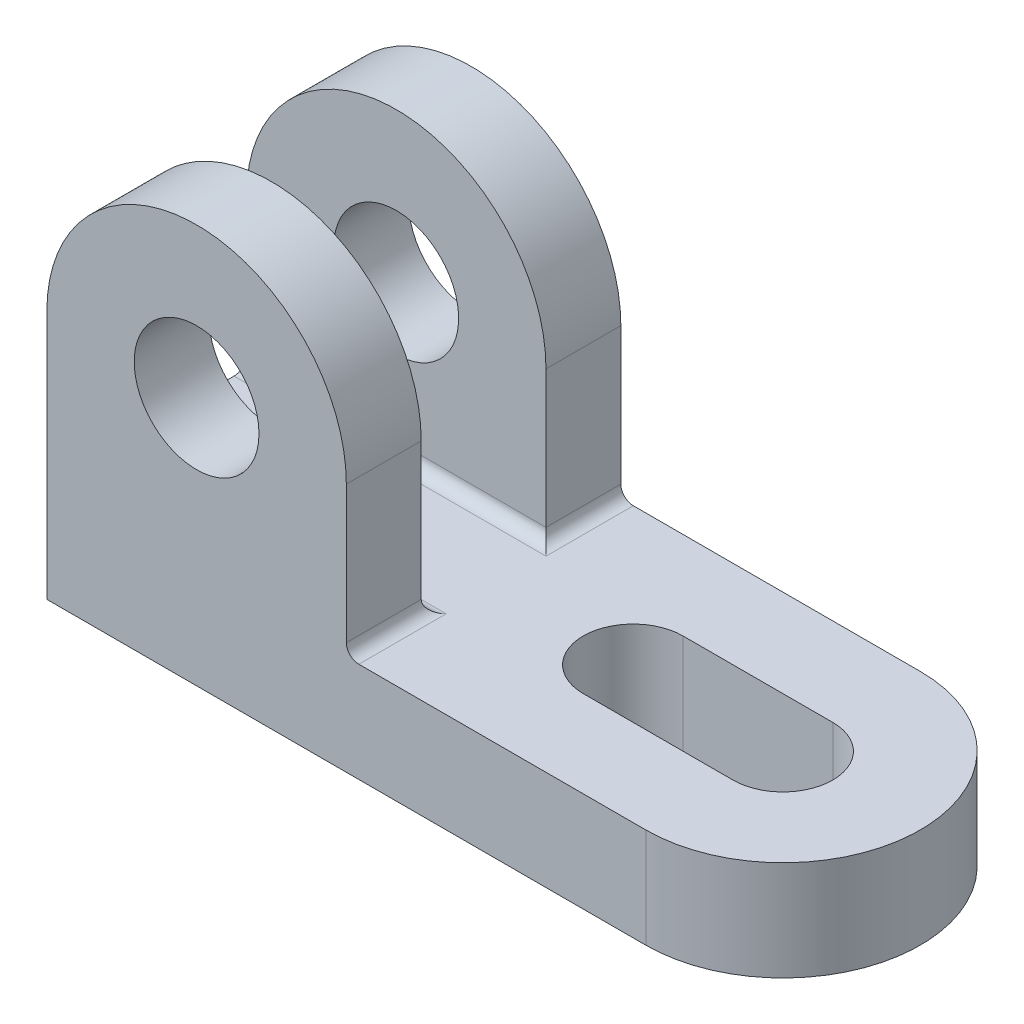
SolidWorks part; units mm, degrees
ref_plane "Front Plane" through (0, 0, 0) normal (0, 0, 1) x (1, 0, 0)
ref_plane "Top Plane" through (0, 0, 0) normal (0, 1, 0) x (1, 0, 0)
ref_plane "Right Plane" through (0, 0, 0) normal (1, 0, 0) x (0, 0, -1)
sketch "Sketch1" plane through (0, 0, 0) normal (0, 1, 0) x (1, 0, 0)
  line L1 (0, 0) -> (96, 0)
  line L2 (0, 0) -> (0, 44)
  line L3 (0, 44) -> (96, 44)
  arc A0 (96, 0) -> (96, 44) centre (96, 22) ccw
  point P6 (96, 0)
  dimension "D3" = 22
  dimension "D1" = 96
  dimension "D2" = 44
extrude "Boss-Extrude1" add sketch "Sketch1" along normal blind 16
sketch "Sketch2" plane through (0, 16, 0) normal (0, 1, 0) x (1, 0, 0)
  line L1 (96.0557, 29.9096) -> (72.0557, 29.9096)
  line L6 (72.0557, 13.9096) -> (96.0557, 13.9096)
  arc A0 (96.0557, 13.9096) -> (96.0557, 29.9096) centre (96.0557, 21.9096) ccw
  arc A1 (72.0557, 29.9096) -> (72.0557, 13.9096) centre (72.0557, 21.9096) ccw
  dimension "D1" = 24
  dimension "D2" = 16
extrude "Cut-Extrude1" cut sketch "Sketch2" against normal up to surface (16 mm away) contours L1 A1 L6 A0 up to face at (53.5, 0, -22)
sketch "Sketch3" plane through (0, 0, 0) normal (0, 0, 1) x (1, 0, 0)
  line L1 (0, 16) -> (48, 16)
  line L2 (0, 16) -> (0, 40)
  line L3 (0, 40) -> (48, 40)
  line L4 (48, 16) -> (48, 40)
  line L5 (0, 0) -> (96, 0) construction
  circle A0 centre (24, 40) radius 24
  circle A1 centre (24, 40) radius 10
  line M6 (96, 16) -> (0, 16)
  dimension "D3" = 20
  dimension "D1" = 40
  dimension "D2" = 48
extrude "Boss-Extrude2" add sketch "Sketch3" against normal blind 12 contours A1 L3 A0 | A1 L3 A0 | A0 L4 M6 | A0 L2 L1
sketch "Sketch8" plane through (0, 0, -44) normal (0, 0, -1) x (-1, 0, 0)
  line L1 (0, 16) -> (-48, 16)
  line L2 (0, 16) -> (0, 40)
  line L4 (-48, 16) -> (-48, 40)
  arc A0 (0, 40) -> (-48, 40) centre (-24, 40) ccw
  circle A1 centre (-24, 40) radius 10
  dimension "D1" = 20
extrude "Boss-Extrude4" add sketch "Sketch8" against normal blind 12
fillet "Fillet1" radius 2 4 edges at (48, 16, -38) (24, 16, -32) (48, 16, -6) (24, 16, -12)
